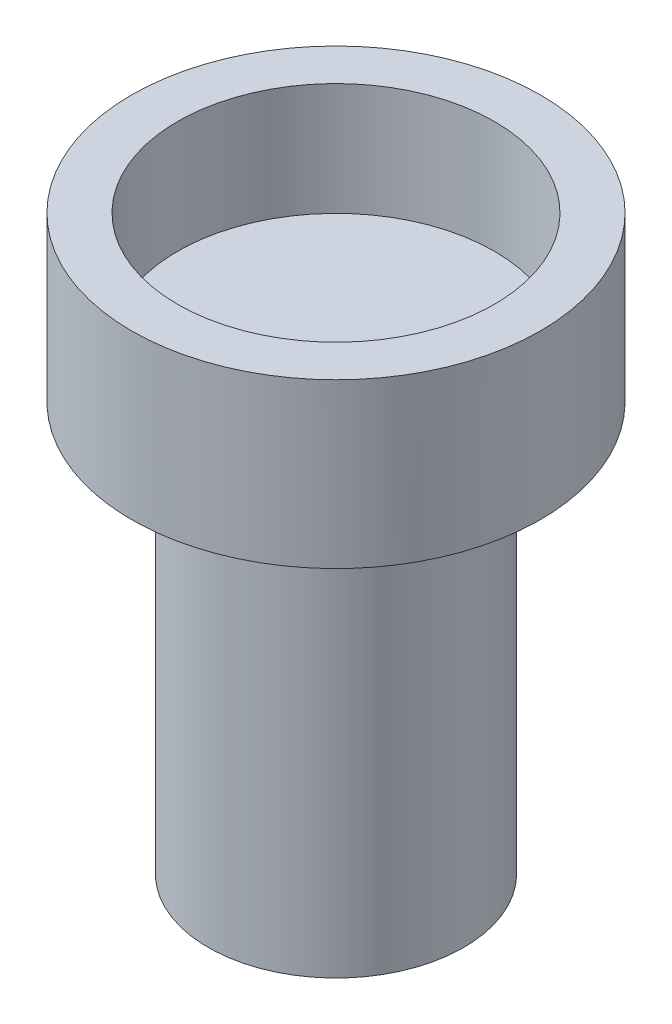
SolidWorks part; units mm, degrees
material "PLA"
ref_plane "Front" through (0, 0, 0) normal (0, 0, 1) x (1, 0, 0)
ref_plane "Top" through (0, 0, 0) normal (0, 1, 0) x (1, 0, 0)
ref_plane "Right" through (0, 0, 0) normal (1, 0, 0) x (0, 0, -1)
other "Configuration Table"
sketch "Esquisse1" plane through (0, 0, 0) normal (0, 1, 0) x (1, 0, 0)
  circle A0 centre (0, 0) radius 3.1
  circle A1 centre (0, 0) radius 4
  dimension "D1" = 6.2
  dimension "D2" = 8
extrude "Boss.-Extru.1" add sketch "Esquisse1" along normal blind 2.2
sketch "Esquisse2" plane through (0, 0, 0) normal (0, -1, 0) x (1, 0, 0)
  circle A0 centre (0, 0) radius 4
extrude "Boss.-Extru.2" add sketch "Esquisse2" along normal blind 1
sketch "Esquisse3" plane through (0, -1, 0) normal (0, -1, 0) x (1, 0, 0)
  circle A0 centre (0, 0) radius 2.5
  dimension "D1" = 5
extrude "Boss.-Extru.3" add sketch "Esquisse3" along normal blind 8
